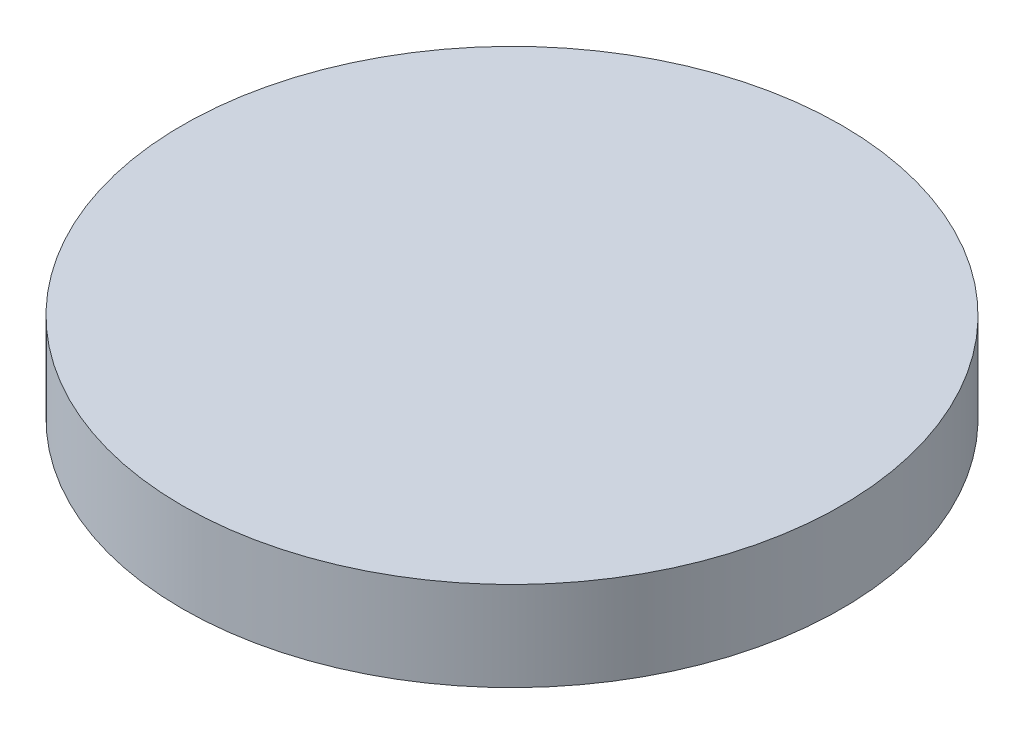
SolidWorks part; units mm, degrees
ref_plane "Front Plane" through (0, 0, 0) normal (0, 0, 1) x (1, 0, 0)
ref_plane "Top Plane" through (0, 0, 0) normal (0, 1, 0) x (1, 0, 0)
ref_plane "Right Plane" through (0, 0, 0) normal (1, 0, 0) x (0, 0, -1)
sketch "Sketch1" plane through (0, 0, 0) normal (0, 1, 0) x (1, 0, 0)
  circle A0 centre (0, 0) radius 36.8971
  dimension "D1" = 73.7942
extrude "Boss-Extrude1" add sketch "Sketch1" along normal blind 10
shell "Shell1" thickness 2
equation "\"Reservoir Capacity\"= 750'mL"
equation "\"Reservoir Height\"= 8 * 2.54'cm"
equation "\"Reservoir Radius\"= \"Reservoir Capacity\" / \"Reservoir Height\" / ( PI ^ 2 )'cm"
equation "\"Reservoir Thickness\"= 0.25'cm"
equation "\"D1@Sketch1\"=(\"Reservoir Radius\" - \"Sliding Tolerance\")*2"
equation "\"Sliding Tolerance\"= 0.5mm"
equation "\"[R][Slider] Height\"= 1"
equation "\"D1@Boss-Extrude1\"=\"[R][Slider] Height\""
equation "\"[R][Slider] Shell Thickness\"= 2mm"
equation "\"D1@Shell1\"=\"[R][Slider] Shell Thickness\""
